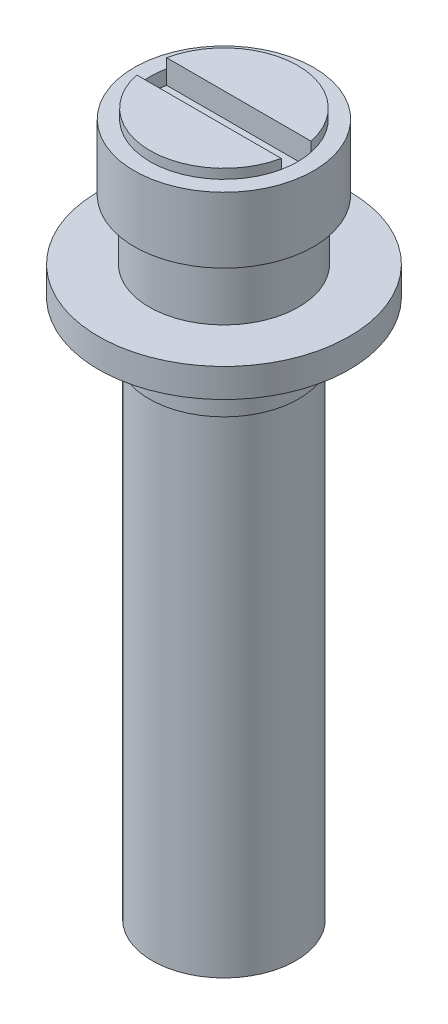
SolidWorks part; units mm, degrees
ref_plane "Plan de face" through (0, 0, 0) normal (0, 0, 1) x (1, 0, 0)
ref_plane "Plan de dessus" through (0, 0, 0) normal (0, 1, 0) x (1, 0, 0)
ref_plane "Plan de droite" through (0, 0, 0) normal (1, 0, 0) x (0, 0, -1)
sketch "Esquisse2" plane through (0, 0, 0) normal (0, 0, 1) x (1, 0, 0)
  line L0 (0, 0) -> (0, 75.6726) construction
  line L1 (0, 64.894) -> (6.175, 64.894)
  line L2 (6.175, 64.894) -> (6.175, 64.094)
  line L3 (6.175, 64.094) -> (7.5, 64.094)
  line L4 (7.5, 64.094) -> (7.5, 58.594)
  line L5 (7.5, 58.594) -> (6.25, 58.594)
  line L6 (6.25, 58.594) -> (6.25, 53.594)
  line L7 (6.25, 53.594) -> (10.5, 53.594)
  line L8 (10.5, 53.594) -> (10.5, 51.194)
  line L9 (10.5, 51.194) -> (6.25, 51.194)
  line L10 (6.25, 51.194) -> (6.25, 46.934)
  line L11 (6.25, 46.934) -> (6, 46.934)
  line L12 (6, 46.934) -> (6, 6.094)
  line L13 (6, 6.094) -> (0, 6.094)
  line L14 (0, 64.894) -> (0, 6.094)
  dimension "D1" = 0.8
  dimension "D2" = 7.5
  dimension "D3" = 5.5
  dimension "D4" = 6.25
  dimension "D5" = 6.175
  dimension "D6" = 2.4
  dimension "D7" = 10.5
  dimension "D8" = 5
  dimension "D9" = 11.66
  dimension "D10" = 58
  dimension "D11" = 6
revolve "Révolution1" add sketch "Esquisse2" angle 360 about L0
sketch "Esquisse3" plane through (0, 64.894, 0) normal (0, 1, 0) x (1, 0, 0)
  line L0 (-6.0472, 1.25) -> (6.0472, 1.25)
  line L1 (0, 0) -> (6.175, 0) construction
  line L2 (-6.0472, -1.25) -> (6.0472, -1.25)
  circle A0 centre (0, 0) radius 6.175 construction
  arc A1 (-6.0472, 1.25) -> (-6.0472, -1.25) centre (0, 0) ccw
  arc A2 (6.0472, 1.25) -> (6.0472, -1.25) centre (0, 0) cw
  dimension "D1" = 2.5
extrude "Enlèv. mat.-Extru.1" cut sketch "Esquisse3" against normal blind 2
